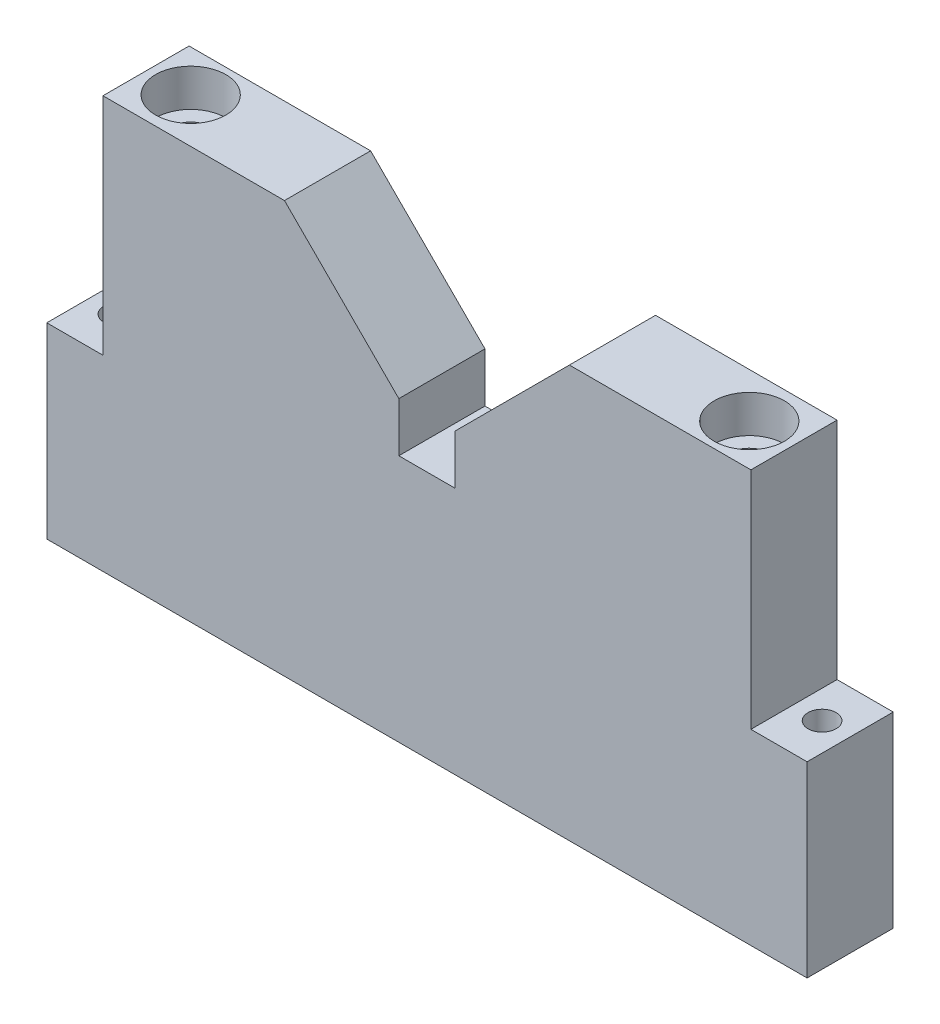
SolidWorks part; units mm, degrees
ref_plane "Спереди" through (0, 0, 0) normal (0, 0, 1) x (1, 0, 0)
ref_plane "Сверху" through (0, 0, 0) normal (0, 1, 0) x (1, 0, 0)
ref_plane "Справа" through (0, 0, 0) normal (1, 0, 0) x (0, 0, -1)
sketch "Эскиз1" plane through (0, 0, 0) normal (0, 0, 1) x (1, 0, 0)
  line L0 (-69.2, -12) -> (-30.4264, -12)
  line L1 (-30.4264, -12) -> (-6, -36.4264)
  line L2 (-6, -36.4264) -> (-6, -47)
  line L3 (-6, -47) -> (6, -47)
  line L4 (6, -47) -> (6, -36.4264)
  line L5 (6, -36.4264) -> (30.4264, -12)
  line L6 (30.4264, -12) -> (69.2, -12)
  line L7 (69.2, -12) -> (69.2, -60)
  line L8 (69.2, -60) -> (-69.2, -60)
  line L9 (-69.2, -60) -> (-69.2, -12)
  circle A0 centre (0, 0) radius 30 construction
  dimension "D1" = 60
  dimension "D3" = 60
  dimension "D2" = 12
  dimension "D4" = 138.4
  dimension "D5" = 12
  dimension "D6" = 35
extrude "Бобышка-Вытянуть1" add sketch "Эскиз1" along normal mid plane 18.4
sketch "Эскиз2" plane through (0, -60, 0) normal (0, -1, 0) x (1, 0, 0)
  line L0 (-81.2, -9.2) -> (81.2, 9.2) construction
  line L1 (-81.2, 9.2) -> (81.2, 9.2)
  line L2 (-81.2, 9.2) -> (-81.2, -9.2)
  line L3 (-81.2, -9.2) -> (81.2, -9.2)
  line L4 (81.2, 9.2) -> (81.2, -9.2)
  line L6 (-69.2, 9.2) -> (69.2, 9.2) construction
  dimension "D1" = 162.4
extrude "Бобышка-Вытянуть2" add sketch "Эскиз2" along normal blind 40
hole_wizard "Цековка для винта с внутренним шестигранником M82" positions "Эскиз12" profile "Эскиз11" counterbore size "M8" standard "ISO" end condition through all
sketch "Эскиз12" plane through (0, -12, 0) normal (0, 1, 0) x (-1, 0, 0)
  line L0 (60, -0.3438) -> (-60, 0.3438) construction
  point P0 (-60, 0.3438)
  point P1 (60, -0.3438)
  dimension "D1" = 120
sketch "Эскиз11" plane through (60, -12, 0.3438) normal (1, 0, 0) x (0, 0, 1)
  line L0 (0, 0) -> (0, 88)
  line L1 (0, 88) -> (4.2, 88)
  line L3 (4.2, 88) -> (4.2, 8)
  line L4 (4.2, 8) -> (7.5, 8)
  line L5 (7.5, 8) -> (7.5, 0)
  line L7 (7.5, 0) -> (0, 0)
  line L11 (0, -6.35) -> (0, 107.95) construction
  dimension "Диаметр сквозного отверстия" = 8.4
  dimension "Глубина сквозного отверстия" = 88
  dimension "Диаметр цековки" = 15
  dimension "Глубина цековки" = 8
hole_wizard "Диаметр отверстия Ø6.0 (6)2" positions "Эскиз14" profile "Эскиз13" hole size "Ø6.0" standard "ISO" end condition through all
sketch "Эскиз14" plane through (0, -60, 0) normal (0, 1, 0) x (-1, 0, 0)
  line L0 (-75.2, 0) -> (75.2, 0) construction
  line L3 (-81.2, -9.2) -> (-81.2, 9.2) construction
  point P0 (-75.2, 0)
  point P1 (75.2, 0)
  dimension "D1" = 6
sketch "Эскиз13" plane through (75.2, -60, 0) normal (1, 0, 0) x (0, 0, 1)
  line L0 (0, 0) -> (0, 40)
  line L1 (0, 40) -> (3, 40)
  line L2 (3, 40) -> (3, 0)
  line L5 (3, 0) -> (0, 0)
  line L11 (0, -6.35) -> (0, 107.95) construction
  dimension "Диаметр сквозного отверстия" = 6
  dimension "Глубина сквозного отверстия" = 40
ref_plane "___mount_plane_1___" through (21.2132, -21.2132, 0) normal (-0.7071, 0.7071, 0) x (0, 0, 1)
ref_plane "___mount_plane_2___" through (-21.2132, -21.2132, 0) normal (0.7071, 0.7071, 0) x (0.7071, -0.7071, 0)
equation "\"D\"= 60"
equation "\"D1@Эскиз1\" = \"D\""
equation "\"D2@Эскиз1\" = \"D\"/5"
equation "\"D3@Эскиз1\" = \"D\""
equation "\"D4@Эскиз1\" = 2*\"D\"+\"Диаметр сквозного отверстия@Эскиз11\"+10"
equation "\"D1@Бобышка-Вытянуть1\" = \"Диаметр сквозного отверстия@Эскиз11\"+10"
equation "\"D1@Эскиз12\" = \"D4@Эскиз1\"- \"Диаметр сквозного отверстия@Эскиз11\"-10"
equation "\"D5@Эскиз1\" = \"D1@Эскиз1\"/5"
equation "\"D6@Эскиз1\" = \"D1@Эскиз1\"/2+5"
equation "\"D1@Эскиз2\" = \"D4@Эскиз1\"+\"Диаметр сквозного отверстия@Эскиз13\"*4"
equation "\"D1@Эскиз14\" = \"Диаметр сквозного отверстия@Эскиз13\""
equation "\"___height_cilynder_locator_base___@Бобышка-Вытянуть2\"=40"
